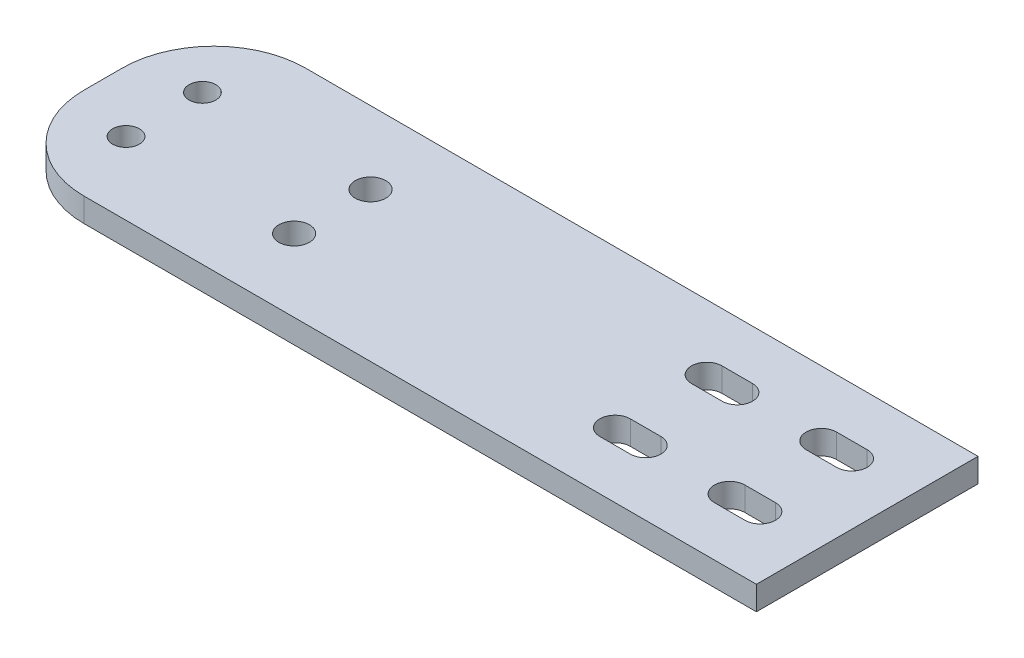
SolidWorks part; units mm, degrees
ref_plane "Front Plane" through (0, 0, 0) normal (0, 0, 1) x (1, 0, 0)
ref_plane "Top Plane" through (0, 0, 0) normal (0, 1, 0) x (1, 0, 0)
ref_plane "Right Plane" through (0, 0, 0) normal (1, 0, 0) x (0, 0, -1)
sketch "Sketch1" plane through (0, 0, 0) normal (0, 1, 0) x (1, 0, 0)
  line L1 (0, 29) -> (200, 29)
  line L2 (0, 29) -> (0, -29)
  line L3 (0, -29) -> (200, -29)
  line L4 (200, 29) -> (200, -29)
  point P4 (0, 0)
  dimension "D1" = 58
  dimension "D2" = 200
extrude "Boss-Extrude1" add sketch "Sketch1" along normal blind 6.25
sketch "Sketch2" plane through (0, 0, 0) normal (0, 1, 0) x (1, 0, 0)
  line L0 (176, 12) -> (184, 12) construction
  line L1 (176, 16) -> (184, 16)
  line L2 (176, 8) -> (184, 8)
  line L3 (200, -29) -> (200, 29) construction
  line L4 (146, 12) -> (154, 12) construction
  line L5 (146, 16) -> (154, 16)
  line L6 (146, 8) -> (154, 8)
  line L7 (146, -12) -> (154, -12) construction
  line L8 (146, -8) -> (154, -8)
  line L9 (146, -16) -> (154, -16)
  line L10 (176, -12) -> (184, -12) construction
  line L11 (176, -8) -> (184, -8)
  line L12 (176, -16) -> (184, -16)
  circle A0 centre (16, 10) radius 3.5
  circle A1 centre (16, -10) radius 3.5
  arc A2 (176, 16) -> (176, 8) centre (176, 12) ccw
  arc A3 (184, 8) -> (184, 16) centre (184, 12) ccw
  arc A4 (146, 16) -> (146, 8) centre (146, 12) ccw
  arc A5 (154, 8) -> (154, 16) centre (154, 12) ccw
  arc A6 (146, -8) -> (146, -16) centre (146, -12) ccw
  arc A7 (154, -16) -> (154, -8) centre (154, -12) ccw
  arc A8 (176, -8) -> (176, -16) centre (176, -12) ccw
  arc A9 (184, -16) -> (184, -8) centre (184, -12) ccw
  point P4 (180, 12)
  point P12 (0, 0)
  point P15 (0, 0)
  point P16 (0, 0)
  point P17 (150, 12)
  point P24 (150, -12)
  point P31 (180, -12)
  point P38 (184, -12)
  dimension "D2" = 7
  dimension "D5" = 4
  dimension "D1" = 16
  dimension "D3" = 20
  dimension "D4" = 10
  dimension "D6" = 12
  dimension "D7" = 8
  dimension "D8" = 20
  dimension "D11" = 30
  dimension "D12" = 24
  dimension "D9" = 2
  dimension "D10" = 2
extrude "Cut-Extrude1" cut sketch "Sketch2" along normal through all
fillet "Fillet1" radius 24 2 edges at (0, 3.125, -29) (0, 3.125, 29)
sketch "Sketch3" plane through (0, 0, 0) normal (0, 1, 0) x (1, 0, 0)
  circle A0 centre (60, -10) radius 4
  circle A1 centre (60, 10) radius 4
  point P4 (0, 0)
  dimension "D4" = 8
  dimension "D1" = 20
  dimension "D2" = 10
  dimension "D3" = 60
extrude "Cut-Extrude2" cut sketch "Sketch3" along normal blind 10
equation "\"D4@Sketch2\"=\"D3@Sketch2\"/2"
